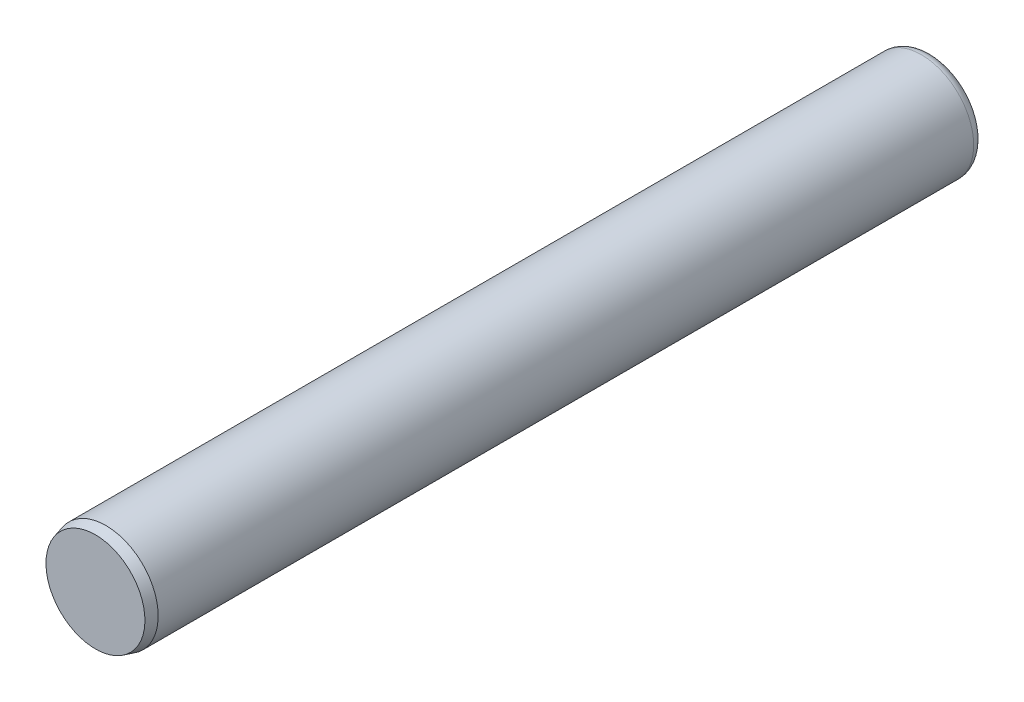
SolidWorks part; units mm, degrees
ref_plane "Front Plane" through (0, 0, 0) normal (0, 0, 1) x (1, 0, 0)
ref_plane "Top Plane" through (0, 0, 0) normal (0, 1, 0) x (1, 0, 0)
ref_plane "Right Plane" through (0, 0, 0) normal (1, 0, 0) x (0, 0, -1)
sketch "Sketch1" plane through (0, 0, 0) normal (0, 0, 1) x (1, 0, 0)
  circle A0 centre (0, 0) radius 0.7938
  point P3 (0, 0.7938)
  dimension "Diameter" = 1.5875
sketch "Sketch2" plane through (0, 0, 0) normal (1, 0, 0) x (0, 0, -1)
  line L0 (-6.35, 0) -> (6.35, 0) construction
  point P2 (0, 0)
  dimension "Length" = 12.7
sketch "Sketch3" plane through (0, 0, 0) normal (1, 0, 0) x (0, 0, -1)
  line L0 (-6.35, 0) -> (-6.35, 0.7512)
  line L1 (-6.35, 0.7512) -> (-6.1913, 0.7938)
  line L2 (-6.1913, 0.7938) -> (6.1912, 0.7938)
  line L3 (6.35, 0.635) -> (6.35, 0)
  line L4 (6.35, 0) -> (-6.35, 0)
  arc A0 (6.1912, 0.7938) -> (6.35, 0.635) centre (6.1913, 0.635) cw
  dimension "D1" = 0.1588
  dimension "D2" = 75
  dimension "D3" = 0.1588
revolve "Revolve1" add sketch "Sketch3" angle 360 about L4
equation "\"D1@Sketch3\"=.1*\"Diameter@Sketch1\""
equation "\"D3@Sketch3\"=.1*\"Diameter@Sketch1\""
